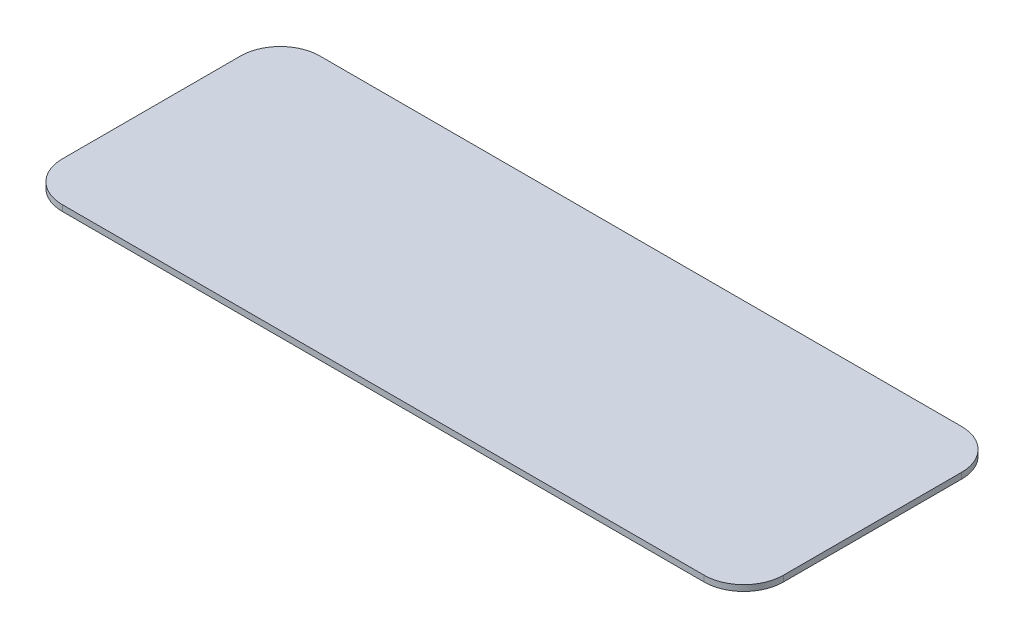
SolidWorks part; units mm, degrees
material "Hexcel AS4C (3000 丝)"
ref_plane "前视基准面" through (0, 0, 0) normal (0, 0, 1) x (1, 0, 0)
ref_plane "上视基准面" through (0, 0, 0) normal (0, 1, 0) x (1, 0, 0)
ref_plane "右视基准面" through (0, 0, 0) normal (1, 0, 0) x (0, 0, -1)
sketch "草图1" plane through (0, 0, 0) normal (0, 1, 0) x (1, 0, 0)
  line L1 (91, -32.5) -> (-91, -32.5)
  line L2 (91, -32.5) -> (91, 32.5)
  line L3 (91, 32.5) -> (-91, 32.5)
  line L4 (-91, -32.5) -> (-91, 32.5)
  line L5 (91, -32.5) -> (-91, 32.5) construction
  line L6 (91, 32.5) -> (-91, -32.5) construction
  point P0 (0, 0)
extrude "凸台-拉伸1" add sketch "草图1" along normal blind 1.5
fillet "圆角1" radius 10 4 edges at (-91, 0.75, -32.5) (91, 0.75, -32.5) (91, 0.75, 32.5) (-91, 0.75, 32.5)
